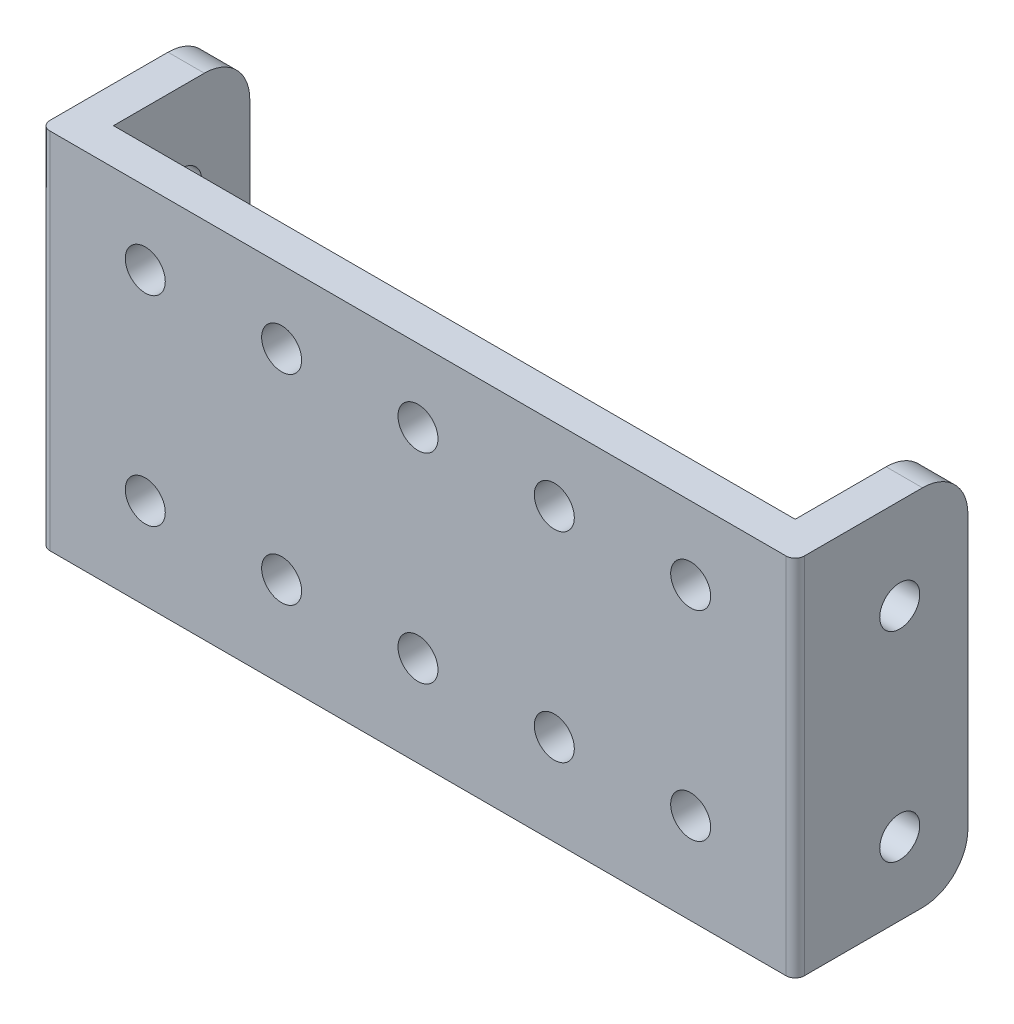
SolidWorks part; units mm, degrees
ref_plane "Front Plane" through (0, 0, 0) normal (0, 0, 1) x (1, 0, 0)
ref_plane "Top Plane" through (0, 0, 0) normal (0, 1, 0) x (1, 0, 0)
ref_plane "Right Plane" through (0, 0, 0) normal (1, 0, 0) x (0, 0, -1)
sketch "Sketch1" plane through (0, 0, 0) normal (0, 1, 0) x (1, 0, 0)
  line L0 (36.5, 0) -> (-36.5, 0)
  line L1 (-37.5, 1) -> (-37.5, 15)
  line L2 (37.5, 1) -> (37.5, 15)
  line L3 (41.5, -3) -> (41.5, 15)
  line L4 (40.5, -4) -> (-40.5, -4)
  line L5 (-41.5, -3) -> (-41.5, 15)
  line L6 (-41.5, 15) -> (-37.5, 15)
  line L7 (37.5, 15) -> (41.5, 15)
  line L8 (41.5, -4) -> (-41.5, -4) construction
  line L9 (-41.5, -4) -> (-41.5, 15) construction
  line L10 (41.5, -4) -> (41.5, 15) construction
  line L11 (37.5, 0) -> (37.5, 15) construction
  line L12 (37.5, 0) -> (-37.5, 0) construction
  line L13 (-37.5, 0) -> (-37.5, 15) construction
  line L14 (-37.5, 1) -> (-37.5, 0)
  line L15 (-37.5, 0) -> (-36.5, 0)
  line L16 (36.5, 0) -> (37.5, 0)
  line L17 (37.5, 0) -> (37.5, 1)
  arc A0 (-40.5, -4) -> (-41.5, -3) centre (-40.5, -3) cw
  arc A1 (41.5, -3) -> (40.5, -4) centre (40.5, -3) cw
  point P4 (0, 0)
  dimension "D2" = 1
  dimension "D1" = 4
extrude "Boss-Extrude1" add sketch "Sketch1" along normal blind 40
fillet "Fillet1" radius 5 4 edges at (-39.5, 0, -15) (-39.5, 40, -15) (39.5, 0, -15) (39.5, 40, -15)
sketch "Sketch2" plane through (0, 0, 4) normal (0, 0, 1) x (1, 0, 0)
  line L0 (-40.5, 40) -> (40.5, 40) construction
  circle A0 centre (-30, 32) radius 2.2
  circle A1 centre (-15, 32) radius 2.2
  circle A2 centre (0, 32) radius 2.2
  circle A3 centre (15, 32) radius 2.2
  circle A4 centre (30, 32) radius 2.2
  circle A5 centre (-30, 10) radius 2.2
  circle A6 centre (-15, 10) radius 2.2
  circle A7 centre (0, 10) radius 2.2
  circle A8 centre (15, 10) radius 2.2
  circle A9 centre (30, 10) radius 2.2
  point P4 (0, 40)
  dimension "D1" = 30
  dimension "D2" = 8
  dimension "D3" = 5
  dimension "D4" = 2
extrude "Cut-Extrude1" cut sketch "Sketch2" against normal blind 40
sketch "Sketch3" plane through (-41.5, 0, 0) normal (-1, 0, 0) x (0, 0, 1)
  line L0 (-15, 35) -> (-15, 5) construction
  line L1 (-10, 0) -> (3, 0) construction
  circle A0 centre (-7.5, 30) radius 2.2
  circle A1 centre (-7.5, 8) radius 2.2
  dimension "D1" = 7.5
  dimension "D2" = 7.5
  dimension "D3" = 22
  dimension "D4" = 8
extrude "Cut-Extrude2" cut sketch "Sketch3" against normal blind 94
